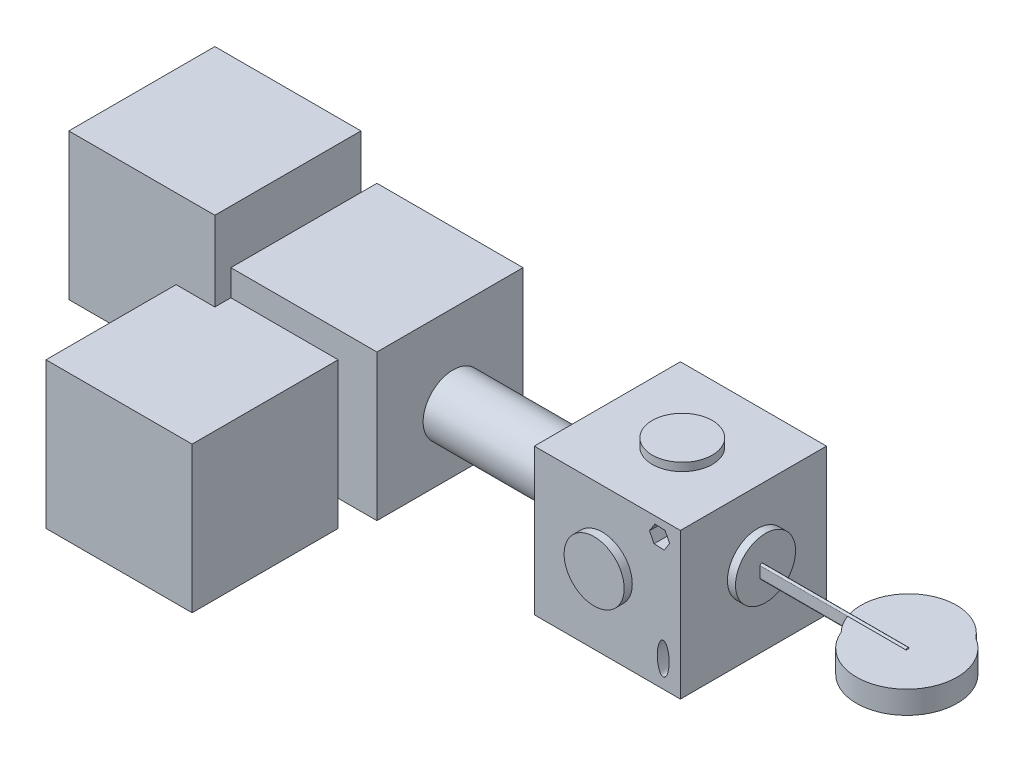
SolidWorks part; units mm, degrees
ref_plane "Front Plane" through (0, 0, 0) normal (0, 0, 1) x (1, 0, 0)
ref_plane "Top Plane" through (0, 0, 0) normal (0, 1, 0) x (1, 0, 0)
ref_plane "Right Plane" through (0, 0, 0) normal (1, 0, 0) x (0, 0, -1)
sketch "Sketch1" plane through (0, 0, 0) normal (0, 0, 1) x (1, 0, 0)
  line L1 (-45, 45) -> (45, 45)
  line L2 (-45, 45) -> (-45, -45)
  line L3 (-45, -45) -> (45, -45)
  line L4 (45, 45) -> (45, -45)
  line L5 (-45, 45) -> (45, -45) construction
  line L6 (-45, -45) -> (45, 45) construction
  point P0 (0, 0)
  dimension "D1" = 90
  dimension "D2" = 90
extrude "Boss-Extrude1" add sketch "Sketch1" along normal blind 90
sketch "Sketch2" plane through (45, 0, 0) normal (1, 0, 0) x (0, 0, -1)
  circle A0 centre (-42.5335, 3.7359) radius 18.4951
extrude "Boss-Extrude2" add sketch "Sketch2" against normal blind 90 and the other way blind 5
sketch "Sketch3" plane through (0, 0, 90) normal (0, 0, 1) x (1, 0, 0)
  circle A0 centre (-3.1268, 1.6243) radius 18.4951
extrude "Boss-Extrude3" add sketch "Sketch3" against normal blind 90 and the other way blind 5
sketch "Sketch4" plane through (0, 45, 0) normal (0, 1, 0) x (0, 0, -1)
  circle A0 centre (-44.963, -1.1407) radius 18.4951
extrude "Boss-Extrude4" add sketch "Sketch4" against normal blind 90 and the other way blind 5
sketch "Sketch5" plane through (-45, 0, 0) normal (-1, 0, 0) x (0, 0, 1)
  circle A0 centre (44.3232, -3.4807) radius 18.4951
extrude "Boss-Extrude5" add sketch "Sketch5" against normal blind 90 and the other way blind 95.6719
sketch "Sketch6" plane through (0, -45, 0) normal (0, -1, 0) x (0, 0, -1)
  circle A0 centre (-43.114, -1.0732) radius 18.4951
extrude "Boss-Extrude6" add sketch "Sketch6" against normal blind 90 and the other way blind 5
sketch "Sketch7" plane through (0, 0, 0) normal (0, 0, -1) x (-1, 0, 0)
  line L1 (-28.8022, 29.8056) -> (-25.9491, 35.3523)
  line L2 (-25.9491, 35.3523) -> (-29.3261, 40.5965)
  line L3 (-29.3261, 40.5965) -> (-35.5562, 40.294)
  line L4 (-35.5562, 40.294) -> (-38.4093, 34.7474)
  line L5 (-38.4093, 34.7474) -> (-35.0323, 29.5031)
  line L6 (-35.0323, 29.5031) -> (-28.8022, 29.8056)
  circle A0 centre (-32.1792, 35.0498) radius 5.4018 construction
extrude "Cut-Extrude1" cut sketch "Sketch7" against normal blind 90
sketch "Sketch8" plane through (0, 0, 90) normal (0, 0, 1) x (1, 0, 0)
  ellipse E0 centre (34.4176, -28.6824) end of major axis (34.4176, -38.4588) minor radius 3.6403
extrude "Cut-Extrude2" cut sketch "Sketch8" against normal blind 90
sketch "Sketch9" plane through (50, 0, 0) normal (1, 0, 0) x (0, 0, -1)
  line L0 (-44.9872, 6.623) -> (-44.9872, 0) construction
  line L1 (-44.0735, 6.623) -> (-44.0735, 0)
  line L2 (-45.9008, 6.623) -> (-45.9008, 0)
  arc A0 (-44.0735, 6.623) -> (-45.9008, 6.623) centre (-44.9872, 6.623) ccw
  arc A1 (-45.9008, 0) -> (-44.0735, 0) centre (-44.9872, 0) ccw
  point P2 (-44.9872, 3.3115)
extrude "Boss-Extrude7" add sketch "Sketch9" along normal blind 90
ref_plane "Plane1" through (140, 6.623, 44.0735) normal (0, 1, 0) x (1, 0, 0)
sketch "Sketch10" plane through (140, 6.623, 44.0735) normal (0, 1, 0) x (1, 0, 0)
  circle A0 centre (-8.4258, 8.1881) radius 29.4355
  circle A1 centre (-0.8539, -0.5784) radius 31.0088
extrude "Boss-Extrude10" add sketch "Sketch10" against normal blind 14 contours A0 | A1
sketch "Sketch11" plane through (-140.6719, 0, 0) normal (-1, 0, 0) x (0, 0, 1)
  line L1 (1.2747, 48.0079) -> (91.2747, 48.0079)
  line L2 (1.2747, 48.0079) -> (1.2747, -41.9921)
  line L3 (1.2747, -41.9921) -> (91.2747, -41.9921)
  line L4 (91.2747, 48.0079) -> (91.2747, -41.9921)
  line L5 (1.2747, 48.0079) -> (91.2747, -41.9921) construction
  line L6 (1.2747, -41.9921) -> (91.2747, 48.0079) construction
  point P0 (46.2747, 3.0079)
  dimension "D1" = 90
  dimension "D2" = 90
extrude "Boss-Extrude11" add sketch "Sketch11" along normal blind 90
sketch "Sketch14" plane through (0, 0, 91.2747) normal (0, 0, 1) x (1, 0, 0)
  line L1 (-254.538, 31.9306) -> (-164.538, 31.9306)
  line L2 (-254.538, 31.9306) -> (-254.538, -58.0694)
  line L3 (-254.538, -58.0694) -> (-164.538, -58.0694)
  line L4 (-164.538, 31.9306) -> (-164.538, -58.0694)
  line L5 (-254.538, 31.9306) -> (-164.538, -58.0694) construction
  line L6 (-254.538, -58.0694) -> (-164.538, 31.9306) construction
  point P0 (-209.538, -13.0694)
  dimension "D1" = 90
  dimension "D2" = 90
extrude "Boss-Extrude12" add sketch "Sketch14" along normal blind 90
sketch "Sketch15" plane through (-230.6719, 0, 0) normal (-1, 0, 0) x (0, 0, 1)
  line L1 (11.1179, 80.8878) -> (101.1179, 80.8878)
  line L2 (11.1179, 80.8878) -> (11.1179, -9.1122)
  line L3 (11.1179, -9.1122) -> (101.1179, -9.1122)
  line L4 (101.1179, 80.8878) -> (101.1179, -9.1122)
  line L5 (11.1179, 80.8878) -> (101.1179, -9.1122) construction
  line L6 (11.1179, -9.1122) -> (101.1179, 80.8878) construction
  point P0 (56.1179, 35.8878)
  dimension "D1" = 90
  dimension "D2" = 90
extrude "Boss-Extrude13" add sketch "Sketch15" along normal blind 90
